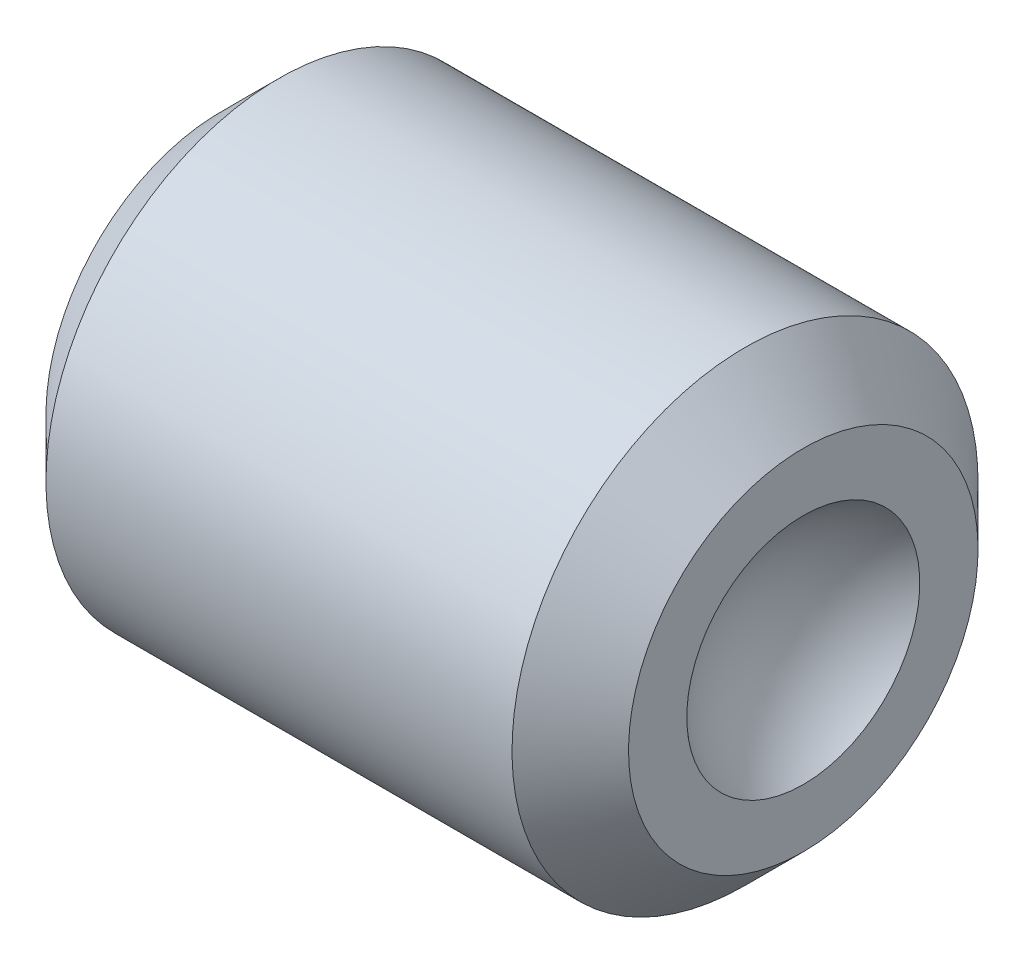
SolidWorks part; units mm, degrees
ref_plane "Front Plane" through (0, 0, 0) normal (0, 0, 1) x (1, 0, 0)
ref_plane "Top Plane" through (0, 0, 0) normal (0, 1, 0) x (1, 0, 0)
ref_plane "Right Plane" through (0, 0, 0) normal (1, 0, 0) x (0, 0, -1)
sketch "Sketch1" plane through (0, 0, 0) normal (0, 0, 1) x (1, 0, 0)
  line L0 (0, 0) -> (0, 1.5)
  line L1 (0, 1.5) -> (0.5, 2)
  line L2 (0.5, 2) -> (4.5, 2)
  line L3 (4.5, 2) -> (5, 1.5)
  line L4 (0, 0) -> (4.5, 0) construction
  line L5 (0.5, 2) -> (0.5, 1.5) construction
  line L6 (0.5, 1.5) -> (0.5, 1) construction
  line L7 (0.5, 1) -> (0.5, 0.5) construction
  line L8 (0.5, 0.5) -> (0.5, 0) construction
  line L9 (0.5, 1.5) -> (0, 1.5) construction
  line L10 (4.5, 2) -> (4.5, 0) construction
  line L11 (5, 1.5) -> (5, 1)
  line L12 (0, 0) -> (4.5, 0)
  arc A0 (4.5, 0) -> (5, 1) centre (5.75, 0) cw
  dimension "D1" = 45
  dimension "D2" = 4
  dimension "D3" = 5
  dimension "D4" = 2
revolve "Revolve1" add sketch "Sketch1" angle 360 about L12
sketch "Sketch2" plane through (0, 0, 0) normal (-1, 0, 0) x (0, 0, 1)
  line L1 (0, 1.1547) -> (-1, 0.5774)
  line L2 (-1, 0.5774) -> (-1, -0.5774)
  line L3 (-1, -0.5774) -> (0, -1.1547)
  line L4 (0, -1.1547) -> (1, -0.5774)
  line L5 (1, -0.5774) -> (1, 0.5774)
  line L6 (1, 0.5774) -> (0, 1.1547)
  circle A0 centre (0, 0) radius 1 construction
  dimension "D1" = 2
extrude "Cut-Extrude1" cut sketch "Sketch2" against normal offset from surface (3 mm away) 2 up to face at (5, -1.5, 0)
